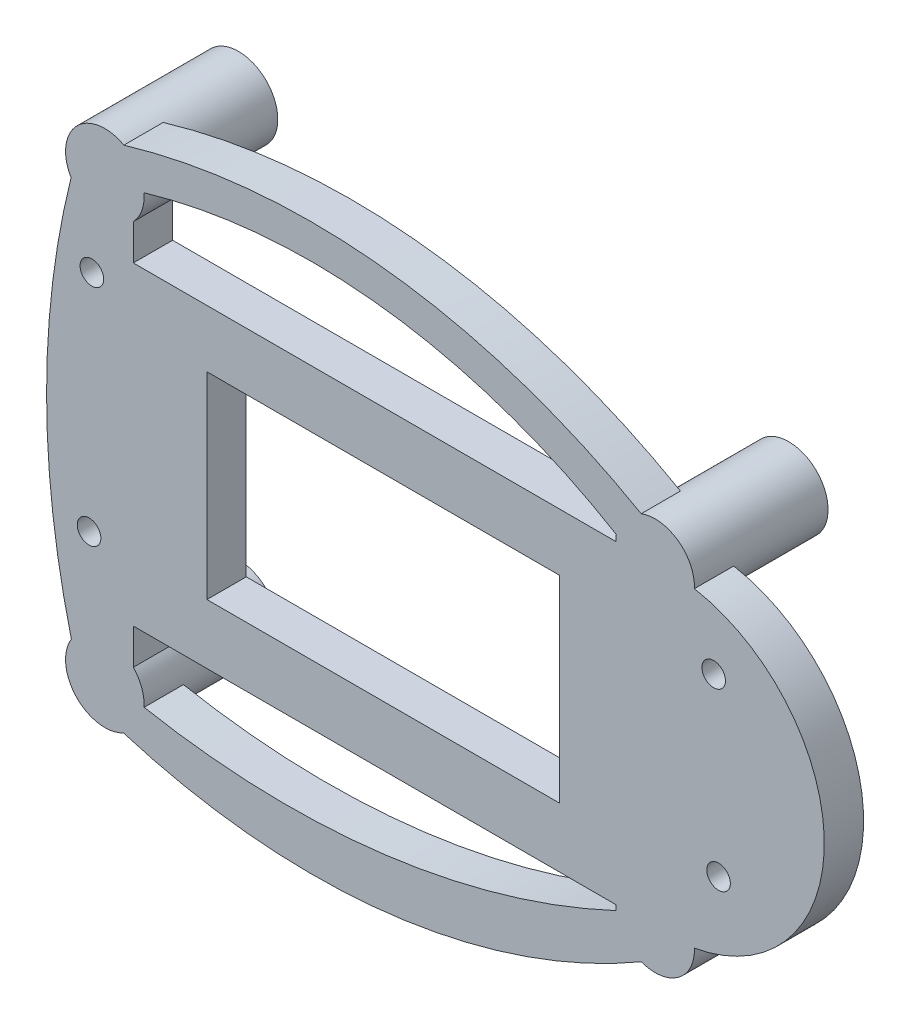
SolidWorks part; units mm, degrees
ref_plane "Front Plane" through (0, 0, 0) normal (0, 0, 1) x (1, 0, 0)
ref_plane "Top Plane" through (0, 0, 0) normal (0, 1, 0) x (1, 0, 0)
ref_plane "Right Plane" through (0, 0, 0) normal (1, 0, 0) x (0, 0, -1)
sketch "Sketch1" plane through (0, 0, 0) normal (0, 0, 1) x (1, 0, 0)
  line L0 (-79.8928, -14.302) -> (-79.8928, -22.302)
  line L1 (-79.8928, 33.698) -> (-79.8928, 25.698)
  line L2 (-79.8928, 25.698) -> (-17.1318, 25.698)
  line L3 (-79.8928, -14.302) -> (-17.1318, -14.302)
  line L4 (-70.5266, 18.3949) -> (-25.7093, 18.3949)
  line L5 (-70.5266, 18.3949) -> (-70.5266, -6.7027)
  line L6 (-70.5266, -6.7027) -> (-25.7093, -6.7027)
  line L7 (-25.7093, 18.3949) -> (-25.7093, -6.7027)
  circle A0 centre (-83.5123, -22.302) radius 2.6
  arc A1 (-87.1275, -22.1248) -> (-83.6009, -25.9204) centre (-83.5123, -22.302) ccw
  circle A2 centre (-83.5123, 33.698) radius 2.6
  arc A3 (-83.5123, 37.3175) -> (-87.1318, 33.698) centre (-83.5123, 33.698) ccw
  circle A4 centre (-13.5123, 25.698) radius 2.6
  arc A5 (-9.8928, 25.698) -> (-13.5123, 29.3175) centre (-13.5123, 25.698) ccw
  circle A6 centre (-13.5123, -14.302) radius 2.6
  arc A7 (-13.5123, -17.9215) -> (-9.8928, -14.302) centre (-13.5123, -14.302) ccw
  arc A8 (-87.1318, 33.698) -> (-87.1275, -22.1248) centre (13.5483, 5.7944) ccw
  arc A9 (-9.8928, 25.698) -> (-9.8928, -14.302) centre (-12.1155, 5.698) cw
  arc A10 (-83.6009, -25.9204) -> (-13.5123, -17.9215) centre (-57.0445, 52.452) ccw
  arc A11 (-13.5123, 29.3175) -> (-83.5123, 37.3175) centre (-57.1669, -42.4104) ccw
  arc A12 (-79.8928, 33.698) -> (-17.1318, 25.698) centre (-57.1829, -38.3237) cw
  arc A13 (-79.8928, -22.302) -> (-17.1318, -14.302) centre (-60.2819, 74.0317) ccw
  circle A14 centre (-85.1672, 22.0113) radius 1.5
  circle A15 centre (-85.5239, -6.7027) radius 1.5
  circle A16 centre (-6.0642, 17.3149) radius 1.5
  circle A17 centre (-5.4453, -4.6911) radius 1.5
extrude "Boss-Extrude1" add sketch "Sketch1" along normal blind 5
sketch "Sketch2" plane through (0, 0, 0) normal (0, 0, -1) x (-1, 0, 0)
  circle A0 centre (13.5123, 25.698) radius 5
  circle A1 centre (13.5123, 25.698) radius 2.6
  circle A2 centre (83.5123, 33.698) radius 2.6
  circle A3 centre (83.5123, 33.698) radius 5
  circle A4 centre (83.5123, 33.698) radius 2.6 construction
  circle A5 centre (83.5123, -22.302) radius 2.6
  circle A6 centre (83.5123, -22.302) radius 5
  circle A7 centre (13.5123, -14.302) radius 2.6
  circle A8 centre (13.5123, -14.302) radius 5
extrude "Boss-Extrude2" add sketch "Sketch2" along normal blind 12 and the other way up to surface other way up to face at (-4.5642, 17.3149, 5)
sketch "Sketch3" plane through (0, 0, 5) normal (0, 0, 1) x (1, 0, 0)
  circle A0 centre (-83.5123, 33.698) radius 2.6
  circle A1 centre (-13.5123, 25.698) radius 2.6
  circle A2 centre (-13.5123, -14.302) radius 2.6
  circle A3 centre (-83.5123, -22.302) radius 2.6
extrude "Boss-Extrude3" add sketch "Sketch3" against normal blind 10
